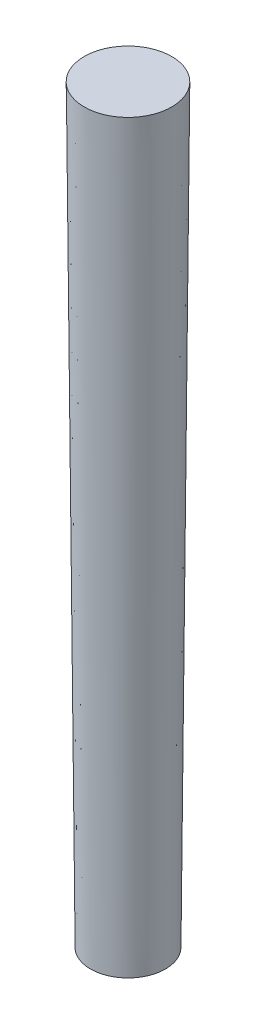
SolidWorks part; units mm, degrees
ref_plane "Front Plane" through (0, 0, 0) normal (0, 0, 1) x (1, 0, 0)
ref_plane "Top Plane" through (0, 0, 0) normal (0, 1, 0) x (1, 0, 0)
ref_plane "Right Plane" through (0, 0, 0) normal (1, 0, 0) x (0, 0, -1)
sketch "Sketch1" plane through (0, 0, 0) normal (0, 1, 0) x (1, 0, 0)
  circle A0 centre (0, 0) radius 3
  dimension "D1" = 6
extrude "Boss-Extrude1" add sketch "Sketch1" along normal blind 60 draft 0.478 draft outward yes
